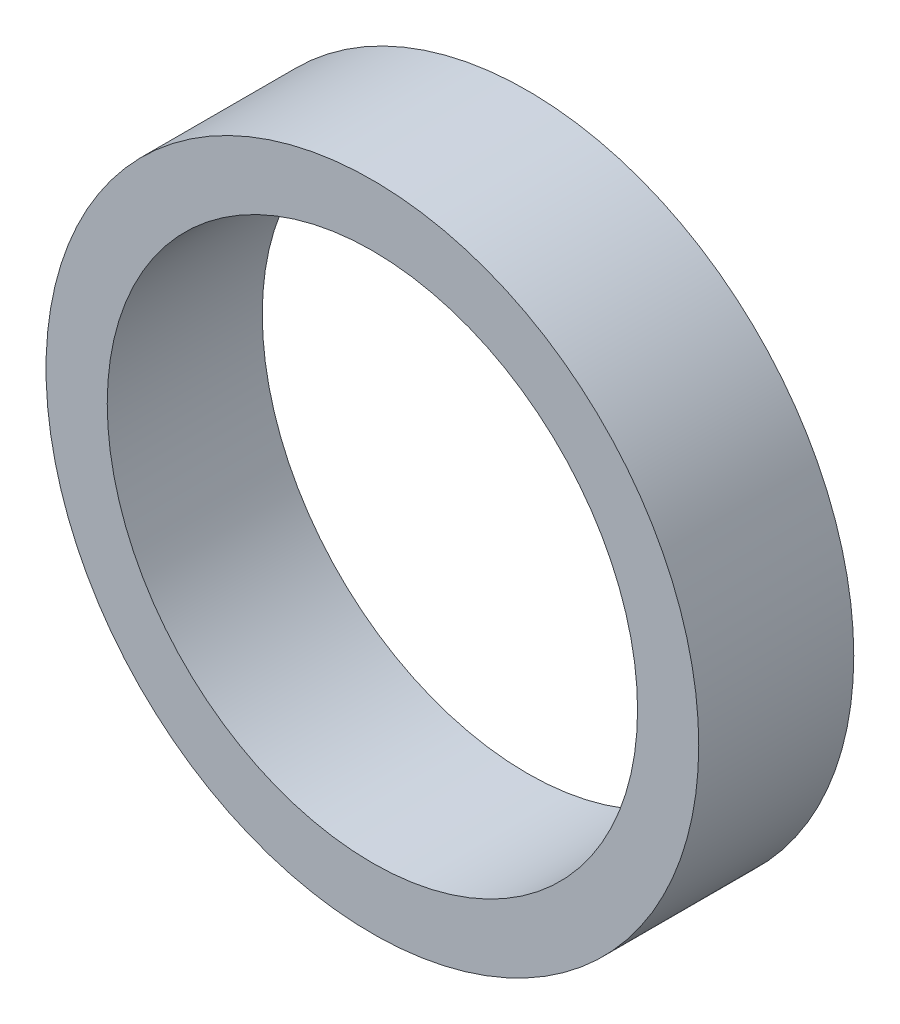
SolidWorks part; units mm, degrees
ref_plane "Front Plane" through (0, 0, 0) normal (0, 0, 1) x (1, 0, 0)
ref_plane "Top Plane" through (0, 0, 0) normal (0, 1, 0) x (1, 0, 0)
ref_plane "Right Plane" through (0, 0, 0) normal (1, 0, 0) x (0, 0, -1)
sketch "Sketch1" plane through (0, 0, 0) normal (0, 0, 1) x (1, 0, 0)
  circle A0 centre (0, 0) radius 32.5
  circle A1 centre (0, 0) radius 40
  dimension "D1" = 65
  dimension "D2" = 80
extrude "Boss-Extrude1" add sketch "Sketch1" along normal blind 19
